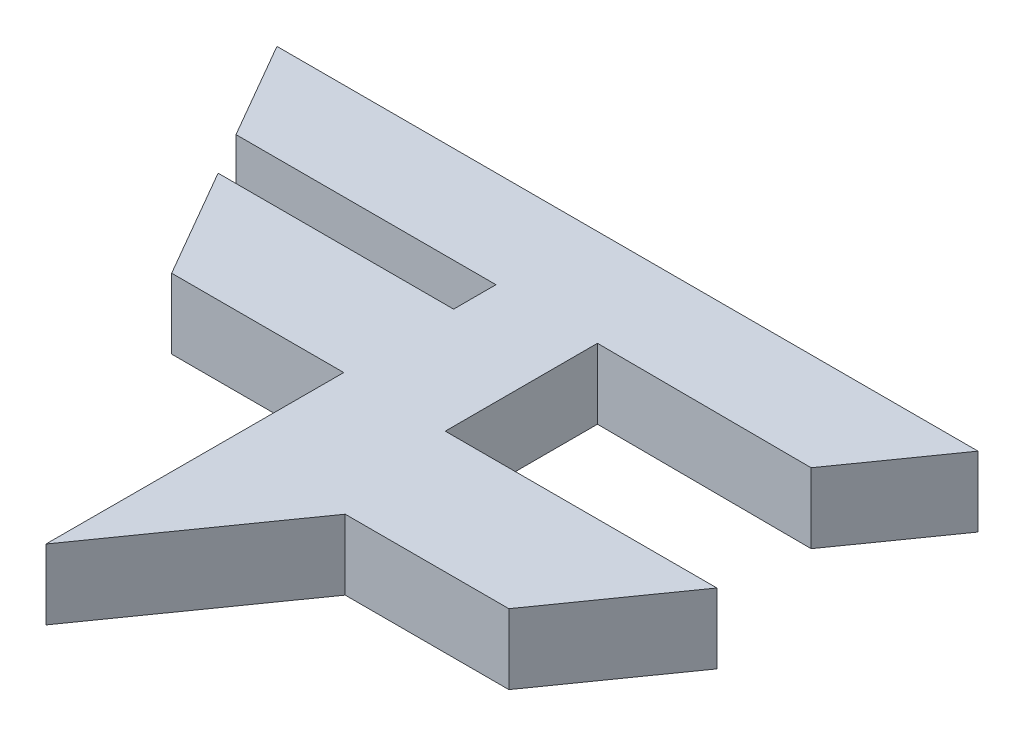
SolidWorks part; units mm, degrees
ref_plane "前视基准面" through (0, 0, 0) normal (0, 0, 1) x (1, 0, 0)
ref_plane "上视基准面" through (0, 0, 0) normal (0, 1, 0) x (1, 0, 0)
ref_plane "右视基准面" through (0, 0, 0) normal (1, 0, 0) x (0, 0, -1)
other "Configuration Table"
sketch "草图1" plane through (0, 0, 0) normal (0, 1, 0) x (1, 0, 0)
  line L0 (-68.1087, 55.7911) -> (31.8913, 55.7911)
  line L1 (-56.588, 35.8367) -> (-47.5965, 20.2629)
  line L2 (22.0433, 41.8352) -> (31.8913, 55.7911)
  line L3 (-8.5841, 20.2629) -> (30.171, 20.2629)
  line L4 (30.171, 20.2629) -> (17.8962, 2.868)
  line L5 (-8.5699, 41.9718) -> (22.0433, 41.8352)
  line L6 (-23.0477, 41.9718) -> (-23.0477, 35.9292)
  line L7 (-8.5699, 25.6006) -> (-8.5699, 20.2629)
  line L8 (-8.5699, 39.8078) -> (-8.5699, 25.6006)
  line L9 (-23.0477, 35.9292) -> (-56.6414, 35.9292)
  line L10 (-23.1763, 20.2629) -> (-47.5965, 20.2629)
  line L11 (17.8962, 2.868) -> (-5.4539, 2.868)
  line L12 (-23.0477, 20.2629) -> (-23.0477, -22.2568)
  line L13 (-8.5699, 39.8078) -> (-8.5699, 41.9718)
  line L14 (-68.1087, 55.7911) -> (31.8913, 55.7911)
  line L16 (-8.5699, 20.2629) -> (30.171, 20.2629)
  line L17 (17.8962, 2.868) -> (-5.4539, 2.868)
  line L18 (-23.1087, -22.1512) -> (-23.1087, 20.2629)
  line L19 (-23.1087, 20.2629) -> (-47.5965, 20.2629)
  line L20 (-60.1301, 41.9718) -> (-68.1087, 55.7911)
  line L21 (-60.1301, 41.9718) -> (-23.0477, 41.9718)
  line L22 (-23.0477, -22.2568) -> (-5.4539, 2.868)
  dimension "D1" = 100
  dimension "D2" = 90
  dimension "D3" = 60
sketch "草图5" plane through (0, 0, 0) normal (0, 1, 0) x (1, 0, 0)
  line L0 (-56.6414, 35.9292) -> (-47.5965, 20.2629)
  line L1 (-47.5965, 20.2629) -> (-23.0477, 20.2629)
  line L2 (-23.0477, 20.2629) -> (-23.1087, -22.1512)
  line L3 (-23.1087, -22.1512) -> (-5.4539, 2.868)
  line L4 (-5.4539, 2.868) -> (17.8962, 2.868)
  line L5 (17.8962, 2.868) -> (30.171, 20.2629)
  line L6 (30.171, 20.2629) -> (-8.5699, 20.2629)
  line L7 (-8.5699, 20.2629) -> (-8.5699, 41.9718)
  line L8 (-8.5699, 41.9718) -> (22.0433, 41.8352)
  line L9 (22.0433, 41.8352) -> (31.8913, 55.7911)
  line L10 (31.8913, 55.7911) -> (-68.1087, 55.7911)
  line L11 (-68.1087, 55.7911) -> (-60.1301, 41.9718)
  line L12 (-60.1301, 41.9718) -> (-23.0477, 41.9718)
  line L13 (-23.0477, 41.9718) -> (-23.0477, 35.9292)
  line L14 (-23.0477, 35.9292) -> (-56.6414, 35.9292)
extrude "凸台-拉伸3" add sketch "草图5" along normal blind 10
